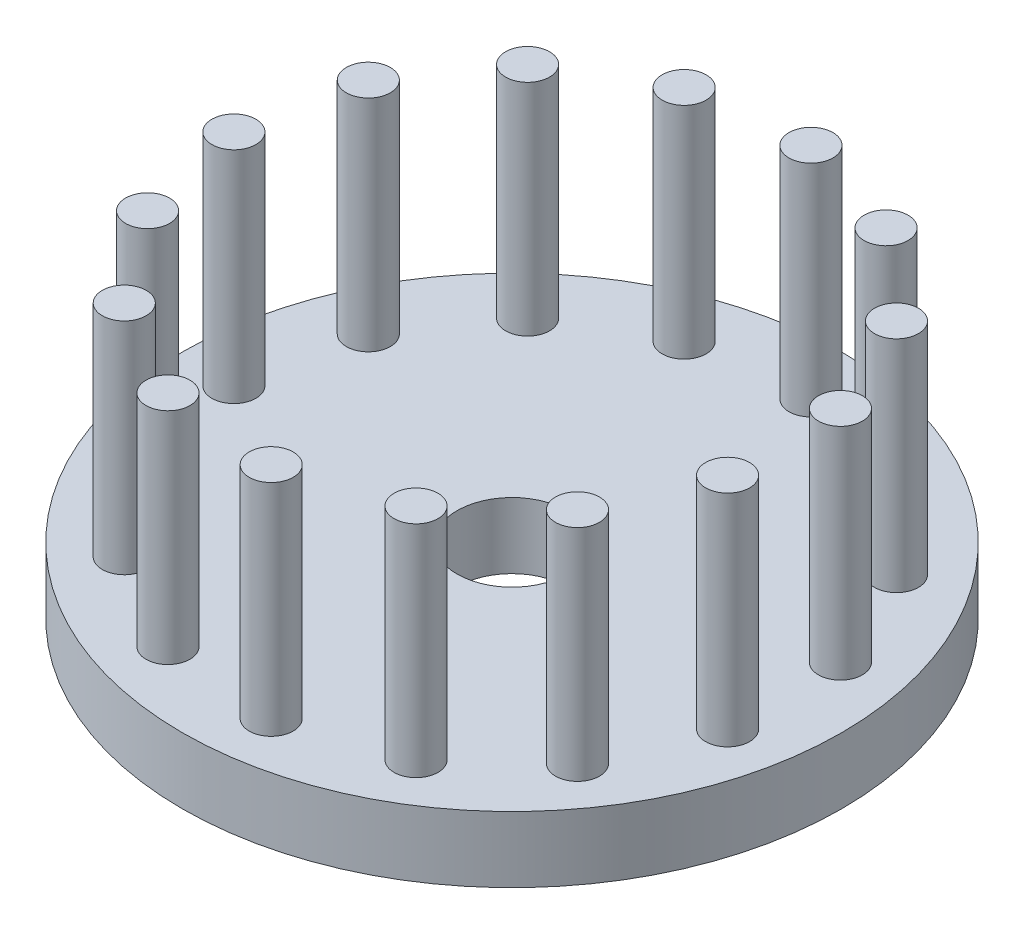
SolidWorks part; units mm, degrees
ref_plane "前基準面" through (0, 0, 0) normal (0, 0, 1) x (1, 0, 0)
ref_plane "上基準面" through (0, 0, 0) normal (0, 1, 0) x (1, 0, 0)
ref_plane "右基準面" through (0, 0, 0) normal (1, 0, 0) x (0, 0, -1)
sketch "草圖1" plane through (0, 0, 0) normal (0, 1, 0) x (1, 0, 0)
  circle A0 centre (0, 0) radius 15
  circle A1 centre (0, 0) radius 2.5
  dimension "D1" = 30
  dimension "D2" = 5
extrude "填料-伸長1" add sketch "草圖1" along normal blind 3
sketch "草圖2" plane through (0, 3, 0) normal (0, 1, 0) x (1, 0, 0)
  circle A0 centre (0, 0) radius 12.5 construction
  circle A1 centre (6.1168, 10.9011) radius 1
  dimension "D1" = 25
  dimension "D2" = 2
extrude "填料-伸長2" add sketch "草圖2" along normal blind 10
pattern_circular "環狀複製排列1" count 15 over 360 about axis through (0, 0, 0) along (0, 1, 0) of "填料-伸長2"
